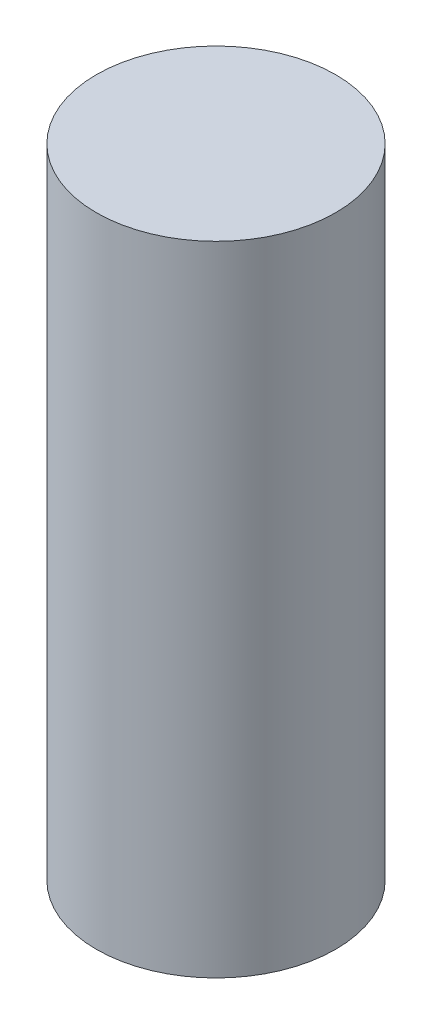
SolidWorks part; units mm, degrees
ref_plane "Front Plane" through (0, 0, 0) normal (0, 0, 1) x (1, 0, 0)
ref_plane "Top Plane" through (0, 0, 0) normal (0, 1, 0) x (1, 0, 0)
ref_plane "Right Plane" through (0, 0, 0) normal (1, 0, 0) x (0, 0, -1)
sketch "Sketch1" plane through (0, 0, 0) normal (0, 1, 0) x (1, 0, 0)
  circle A0 centre (0, 0) radius 0.375
  dimension "D1" = 0.75
extrude "Boss-Extrude1" add sketch "Sketch1" along normal blind 2
